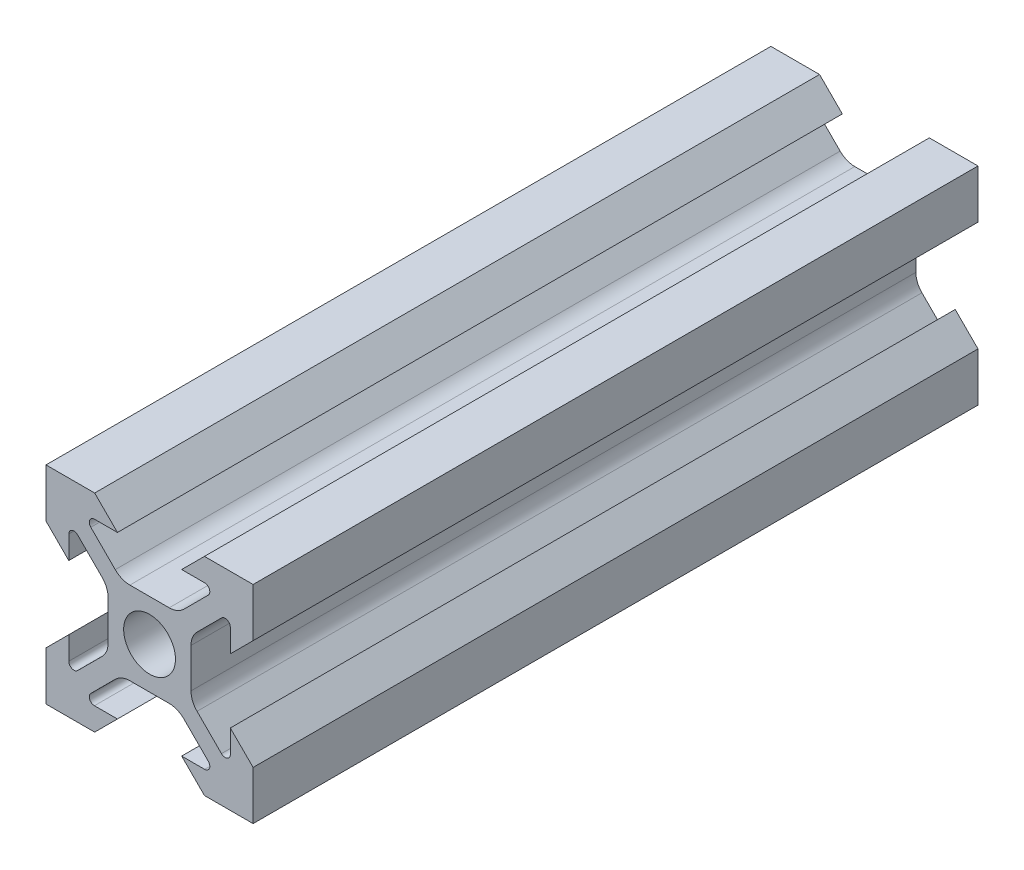
SolidWorks part; units mm, degrees
ref_plane "Front Plane" through (0, 0, 0) normal (0, 0, 1) x (1, 0, 0)
ref_plane "Top Plane" through (0, 0, 0) normal (0, 1, 0) x (1, 0, 0)
ref_plane "Right Plane" through (0, 0, 0) normal (1, 0, 0) x (0, 0, -1)
sketch "Sketch1" plane through (0, 0, 0) normal (0, 0, 1) x (1, 0, 0)
  line L0 (0, 0) -> (0, 10) construction
  line L1 (0, 10) -> (-10, 10) construction
  line L2 (-10, 10) -> (-10, 0) construction
  line L3 (-10, 0) -> (0, 0) construction
  line L4 (0, 0) -> (-10, 10) construction
  line L5 (-10, 10) -> (-10, 5.3)
  line L6 (-10, 5.3) -> (-7.8, 3.1)
  line L7 (-7.8, 3.1) -> (-7.8, 5.3201)
  line L8 (-6.9464, 5.6737) -> (-4.5858, 3.313)
  line L9 (-4, 1.8988) -> (-4, 0)
  line L10 (-10, 10) -> (-5.3, 10)
  line L11 (-5.3, 10) -> (-3.1, 7.8)
  line L12 (-3.1, 7.8) -> (-5.3201, 7.8)
  line L13 (-5.6737, 6.9464) -> (-3.313, 4.5858)
  line L14 (-1.8988, 4) -> (0, 4)
  line L15 (10, 10) -> (5.3, 10)
  line L16 (5.3, 10) -> (3.1, 7.8)
  line L17 (3.1, 7.8) -> (5.3201, 7.8)
  line L18 (5.6737, 6.9464) -> (3.313, 4.5858)
  line L19 (1.8988, 4) -> (0, 4)
  line L20 (10, 10) -> (10, 5.3)
  line L21 (10, 5.3) -> (7.8, 3.1)
  line L22 (7.8, 3.1) -> (7.8, 5.3201)
  line L23 (6.9464, 5.6737) -> (4.5858, 3.313)
  line L24 (4, 1.8988) -> (4, 0)
  line L25 (0, 0) -> (10, 0) construction
  line L26 (10, 0) -> (10, 10) construction
  line L27 (10, 10) -> (0, 10) construction
  line L28 (0, 10) -> (0, 0) construction
  line L29 (0, 0) -> (10, 10) construction
  line L30 (10, -10) -> (10, -5.3)
  line L31 (10, -5.3) -> (7.8, -3.1)
  line L32 (7.8, -3.1) -> (7.8, -5.3201)
  line L33 (6.9464, -5.6737) -> (4.5858, -3.313)
  line L34 (4, -1.8988) -> (4, 0)
  line L35 (10, -10) -> (5.3, -10)
  line L36 (5.3, -10) -> (3.1, -7.8)
  line L37 (3.1, -7.8) -> (5.3201, -7.8)
  line L38 (5.6737, -6.9464) -> (3.313, -4.5858)
  line L39 (1.8988, -4) -> (0, -4)
  line L40 (0, 0) -> (0, -10) construction
  line L41 (0, -10) -> (10, -10) construction
  line L42 (10, -10) -> (10, 0) construction
  line L43 (10, 0) -> (0, 0) construction
  line L44 (0, 0) -> (10, -10) construction
  line L45 (-10, -10) -> (-5.3, -10)
  line L46 (-5.3, -10) -> (-3.1, -7.8)
  line L47 (-3.1, -7.8) -> (-5.3201, -7.8)
  line L48 (-5.6737, -6.9464) -> (-3.313, -4.5858)
  line L49 (-1.8988, -4) -> (0, -4)
  line L50 (-10, -10) -> (-10, -5.3)
  line L51 (-10, -5.3) -> (-7.8, -3.1)
  line L52 (-7.8, -3.1) -> (-7.8, -5.3201)
  line L53 (-6.9464, -5.6737) -> (-4.5858, -3.313)
  line L54 (-4, -1.8988) -> (-4, 0)
  line L55 (0, 0) -> (-10, 0) construction
  line L56 (-10, 0) -> (-10, -10) construction
  line L57 (-10, -10) -> (0, -10) construction
  line L58 (0, -10) -> (0, 0) construction
  line L59 (0, 0) -> (-10, -10) construction
  circle A0 centre (0, 0) radius 2.5
  arc A1 (-7.8, 5.3201) -> (-6.9464, 5.6737) centre (-7.3, 5.3201) cw
  arc A2 (-4.5858, 3.313) -> (-4, 1.8988) centre (-6, 1.8988) cw
  arc A3 (-5.3201, 7.8) -> (-5.6737, 6.9464) centre (-5.3201, 7.3) ccw
  arc A4 (-3.313, 4.5858) -> (-1.8988, 4) centre (-1.8988, 6) ccw
  arc A5 (5.3201, 7.8) -> (5.6737, 6.9464) centre (5.3201, 7.3) cw
  arc A6 (3.313, 4.5858) -> (1.8988, 4) centre (1.8988, 6) cw
  arc A7 (7.8, 5.3201) -> (6.9464, 5.6737) centre (7.3, 5.3201) ccw
  arc A8 (4.5858, 3.313) -> (4, 1.8988) centre (6, 1.8988) ccw
  arc A9 (7.8, -5.3201) -> (6.9464, -5.6737) centre (7.3, -5.3201) cw
  arc A10 (4.5858, -3.313) -> (4, -1.8988) centre (6, -1.8988) cw
  arc A11 (5.3201, -7.8) -> (5.6737, -6.9464) centre (5.3201, -7.3) ccw
  arc A12 (3.313, -4.5858) -> (1.8988, -4) centre (1.8988, -6) ccw
  arc A13 (-5.3201, -7.8) -> (-5.6737, -6.9464) centre (-5.3201, -7.3) cw
  arc A14 (-3.313, -4.5858) -> (-1.8988, -4) centre (-1.8988, -6) cw
  arc A15 (-7.8, -5.3201) -> (-6.9464, -5.6737) centre (-7.3, -5.3201) ccw
  arc A16 (-4.5858, -3.313) -> (-4, -1.8988) centre (-6, -1.8988) ccw
  dimension "D1" = 5
  dimension "D5" = 2
  dimension "D7" = 0.5
  dimension "D2" = 10
  dimension "D3" = 5.3
  dimension "D4" = 6
  dimension "D6" = 0.9
  dimension "D8" = 3.1
  dimension "D10" = 20
  dimension "D9" = 4
extrude "Boss-Extrude1" add sketch "Sketch1" along normal blind 70
